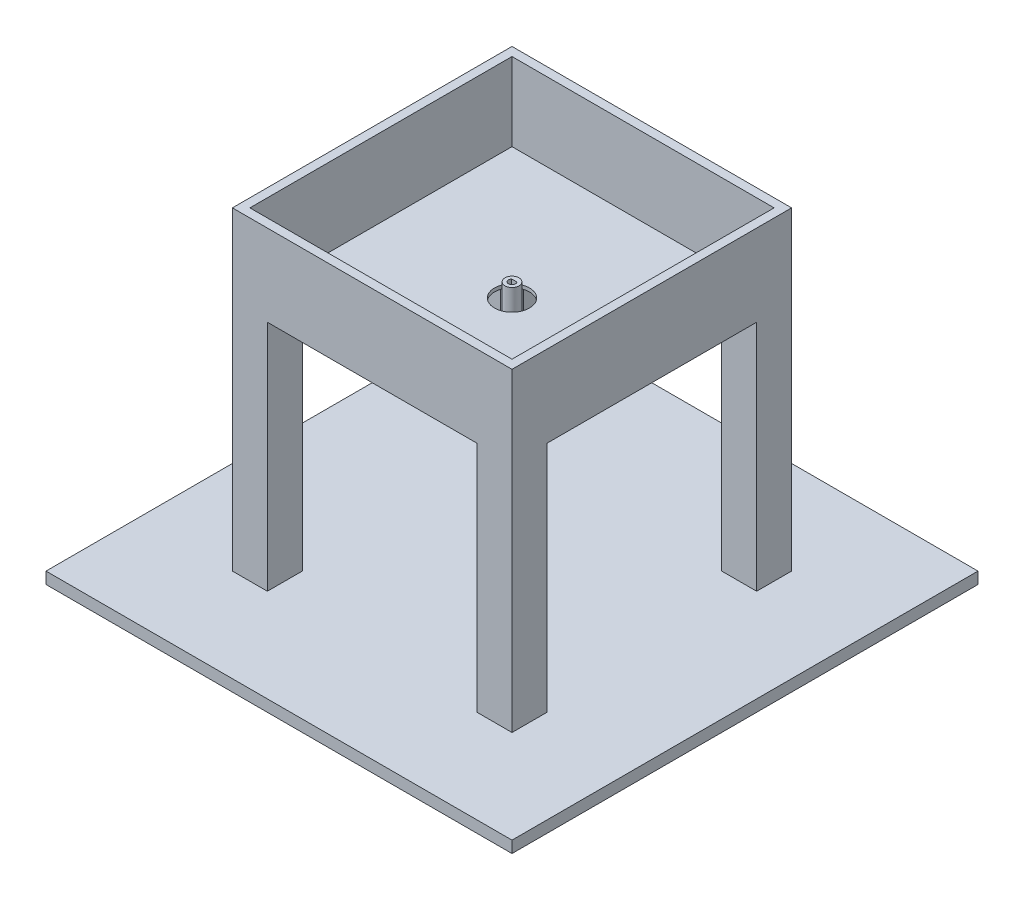
SolidWorks part; units mm, degrees
ref_plane "前视基准面" through (0, 0, 0) normal (0, 0, 1) x (1, 0, 0)
ref_plane "上视基准面" through (0, 0, 0) normal (0, 1, 0) x (1, 0, 0)
ref_plane "右视基准面" through (0, 0, 0) normal (1, 0, 0) x (0, 0, -1)
sketch "草图1" plane through (0, 0, 0) normal (0, 1, 0) x (1, 0, 0)
  line L1 (-56.25, 56.25) -> (56.25, 56.25)
  line L2 (-56.25, 56.25) -> (-56.25, -56.25)
  line L3 (-56.25, -56.25) -> (56.25, -56.25)
  line L4 (56.25, 56.25) -> (56.25, -56.25)
  line L5 (-56.25, 56.25) -> (56.25, -56.25) construction
  line L6 (-56.25, -56.25) -> (56.25, 56.25) construction
  point P0 (0, 0)
  dimension "D1" = 112.5
  dimension "D2" = 112.5
extrude "凸台-拉伸1" add sketch "草图1" along normal blind 1.5
ref_plane "基准面1" through (0, 1.5, 0) normal (0, 1, 0) x (1, 0, 0)
sketch "草图2" plane through (0, 1.5, 0) normal (0, 1, 0) x (1, 0, 0)
  circle A0 centre (0, 0) radius 3
  dimension "D1" = 6
extrude "凸台-拉伸2" add sketch "草图2" along normal blind 6
ref_plane "基准面2" through (0, 7.5, 0) normal (0, 1, 0) x (1, 0, 0)
sketch "草图3" plane through (0, 7.5, 0) normal (0, 1, 0) x (1, 0, 0)
  line L0 (-1.118, 1) -> (1.118, 1)
  arc A0 (-1.118, 1) -> (1.118, 1) centre (0, 0) ccw
  point P5 (0, 1)
  dimension "D1" = 3
  dimension "D2" = 1
extrude "切除-拉伸1" cut sketch "草图3" against normal blind 6
sketch "草图4" plane through (0, 0, 0) normal (0, 1, 0) x (1, 0, 0)
  line L1 (-60, -60) -> (60, -60)
  line L2 (-60, -60) -> (-60, 60)
  line L3 (-60, 60) -> (60, 60)
  line L4 (60, -60) -> (60, 60)
  line L5 (-60, -60) -> (60, 60) construction
  line L6 (-60, 60) -> (60, -60) construction
  line L7 (-56.25, -56.25) -> (56.25, -56.25)
  line L8 (-56.25, -56.25) -> (-56.25, 56.25)
  line L9 (-56.25, 56.25) -> (56.25, 56.25)
  line L10 (56.25, -56.25) -> (56.25, 56.25)
  line L11 (-56.25, -56.25) -> (56.25, 56.25) construction
  line L12 (-56.25, 56.25) -> (56.25, -56.25) construction
  point P0 (0, 0)
  point P6 (0, 0)
  dimension "D1" = 120
  dimension "D2" = 120
extrude "凸台-拉伸3" add sketch "草图4" along normal blind 35
sketch "草图5" plane through (0, 0, 0) normal (0, 1, 0) x (1, 0, 0)
  line L0 (-60, -60) -> (60, -60) construction
  line L1 (-60, -60) -> (-45, -60)
  line L2 (-60, -60) -> (-60, -45)
  line L3 (-60, -45) -> (-45, -45)
  line L4 (-45, -60) -> (-45, -45)
  line L5 (60, -60) -> (45, -60)
  line L6 (60, -60) -> (60, -45)
  line L7 (60, -45) -> (45, -45)
  line L8 (45, -60) -> (45, -45)
  line L9 (60, 60) -> (45, 60)
  line L10 (60, 60) -> (60, 45)
  line L11 (60, 45) -> (45, 45)
  line L12 (45, 60) -> (45, 45)
  line L13 (60, -60) -> (60, 60) construction
  line L15 (-60, 60) -> (-45, 60)
  line L16 (-60, 60) -> (-60, 45)
  line L17 (-60, 45) -> (-45, 45)
  line L18 (-45, 60) -> (-45, 45)
  dimension "D1" = 15
  dimension "D2" = 15
  dimension "D3" = 15
  dimension "D4" = 15
extrude "凸台-拉伸4" add sketch "草图5" against normal blind 100
ref_plane "基准面3" through (0, -100, 0) normal (0, -1, 0) x (-1, 0, 0)
sketch "草图6" plane through (0, -100, 0) normal (0, -1, 0) x (-1, 0, 0)
  line L1 (-100, 100) -> (100, 100)
  line L2 (-100, 100) -> (-100, -100)
  line L3 (-100, -100) -> (100, -100)
  line L4 (100, 100) -> (100, -100)
  line L5 (-100, 100) -> (100, -100) construction
  line L6 (-100, -100) -> (100, 100) construction
  point P0 (0, 0)
  dimension "D1" = 200
  dimension "D2" = 200
extrude "凸台-拉伸5" add sketch "草图6" along normal blind 5
sketch "草图7" plane through (0, 1.5, 0) normal (0, 1, 0) x (1, 0, 0)
  circle A0 centre (0, 0) radius 7.5
  dimension "D1" = 15
extrude "切除-拉伸3" cut sketch "草图7" against normal up to next
ref_plane "基准面4" through (0, 1.5, 0) normal (0, -1, 0) x (-1, 0, 0)
sketch "草图8" plane through (0, 1.5, 0) normal (0, -1, 0) x (-1, 0, 0)
  circle A0 centre (0, 0) radius 3
extrude "凸台-拉伸6" add sketch "草图8" along normal blind 20
ref_plane "基准面5" through (0, -18.5, 0) normal (0, -1, 0) x (-1, 0, 0)
sketch "草图9" plane through (0, -18.5, 0) normal (0, -1, 0) x (-1, 0, 0)
  line L1 (-15, 15) -> (15, 15)
  line L2 (-15, 15) -> (-15, -15)
  line L3 (-15, -15) -> (15, -15)
  line L4 (15, 15) -> (15, -15)
  line L5 (-15, 15) -> (15, -15) construction
  line L6 (-15, -15) -> (15, 15) construction
  point P0 (0, 0)
  dimension "D1" = 30
  dimension "D2" = 30
extrude "凸台-拉伸7" add sketch "草图9" along normal blind 2 separate body
ref_plane "基准面6" through (0, -18.5, 0) normal (0, 1, 0) x (1, 0, 0)
sketch "草图10" plane through (0, -18.5, 0) normal (0, 1, 0) x (1, 0, 0)
  line L0 (15, -15) -> (-15, -15) construction
  line L1 (-15, 15) -> (-10, 15)
  line L2 (-15, 15) -> (-15, 10)
  line L3 (-15, 10) -> (-10, 10)
  line L4 (-10, 15) -> (-10, 10)
  line L5 (15, -15) -> (10, -15)
  line L6 (15, -15) -> (15, -10)
  line L7 (15, -10) -> (10, -10)
  line L8 (10, -15) -> (10, -10)
  line L9 (15, 15) -> (15, -15) construction
  line L11 (15, 15) -> (10, 15)
  line L12 (15, 15) -> (15, 10)
  line L13 (15, 10) -> (10, 10)
  line L14 (10, 15) -> (10, 10)
  line L15 (-15, -15) -> (-10, -15)
  line L16 (-15, -15) -> (-15, -10)
  line L17 (-15, -10) -> (-10, -10)
  line L18 (-10, -15) -> (-10, -10)
  dimension "D1" = 5
  dimension "D2" = 5
  dimension "D3" = 5
  dimension "D4" = 5
extrude "凸台-拉伸8" add sketch "草图10" along normal up to next
